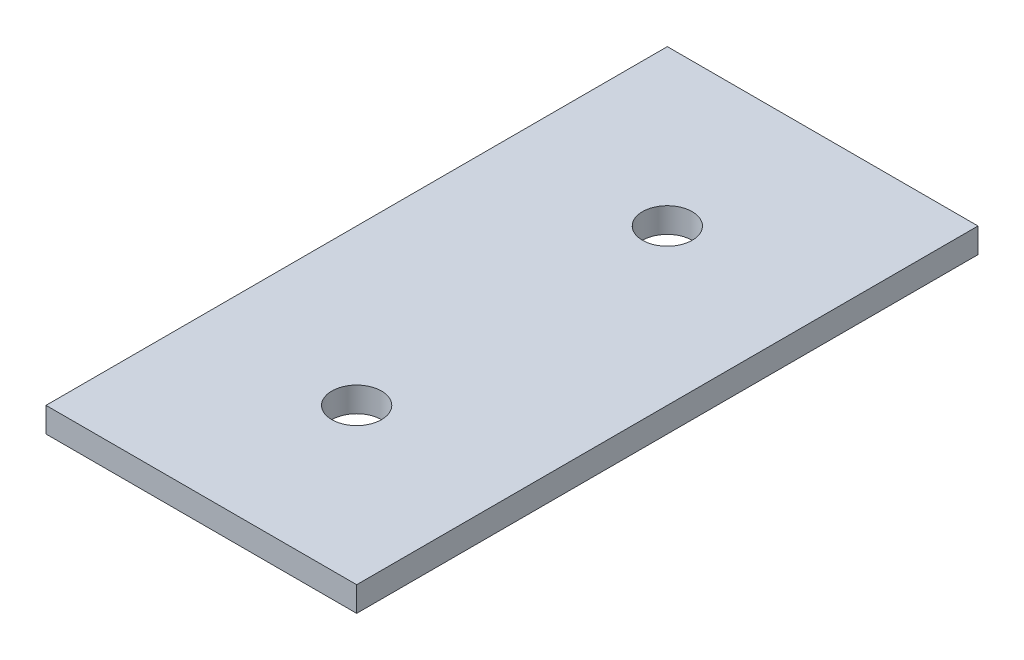
SolidWorks part; units mm, degrees
ref_plane "Front Plane" through (0, 0, 0) normal (0, 0, 1) x (1, 0, 0)
ref_plane "Top Plane" through (0, 0, 0) normal (0, 1, 0) x (1, 0, 0)
ref_plane "Right Plane" through (0, 0, 0) normal (1, 0, 0) x (0, 0, -1)
sketch "Sketch1" plane through (0, 0, 0) normal (0, 1, 0) x (1, 0, 0)
  line L1 (0, 0) -> (50, 0)
  line L2 (0, 0) -> (0, 100)
  line L3 (0, 100) -> (50, 100)
  line L4 (50, 0) -> (50, 100)
  dimension "D1" = 50
  dimension "D2" = 100
extrude "Boss-Extrude1" add sketch "Sketch1" along normal blind 4
sketch "Sketch2" plane through (0, 4, 0) normal (0, 1, 0) x (1, 0, 0)
  line L1 (50, 100) -> (0, 100) construction
  line L2 (0, 100) -> (0, 0) construction
  line L3 (50, 0) -> (50, 100) construction
  circle A0 centre (25, 75) radius 4
  circle A2 centre (25, 25) radius 4
  point P2 (0, 0)
  point P3 (0, 0)
  dimension "D1" = 50
  dimension "D2" = 8
  dimension "D3" = 25
  dimension "D4" = 8
  dimension "D6" = 25
  dimension "D9" = 25
extrude "Cut-Extrude1" cut sketch "Sketch2" against normal through all
